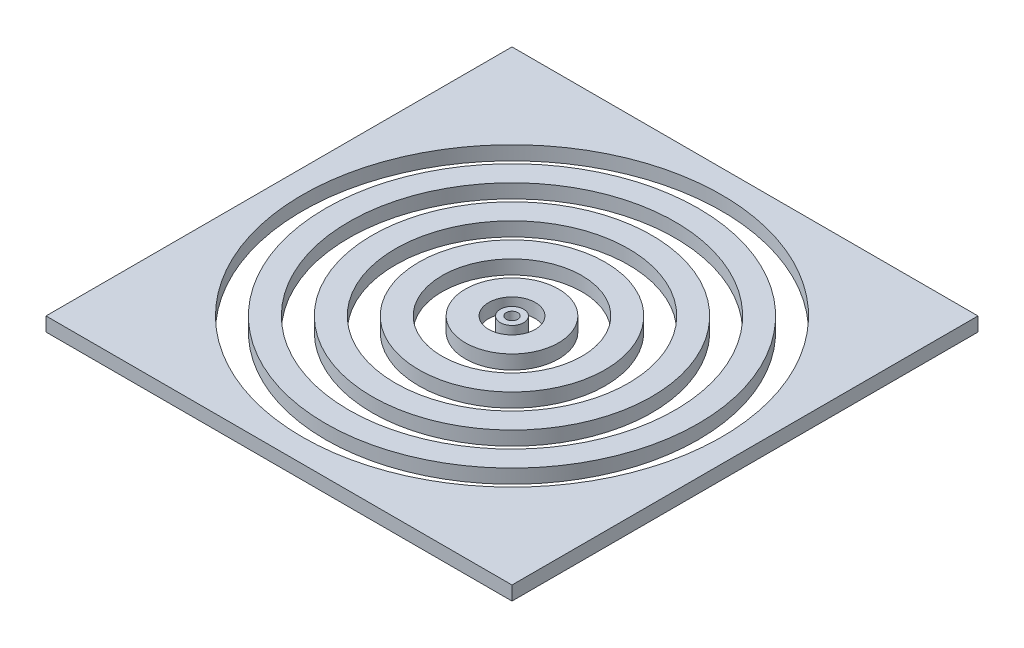
SolidWorks part; units mm, degrees
ref_plane "Front Plane" through (0, 0, 0) normal (0, 0, 1) x (1, 0, 0)
ref_plane "Top Plane" through (0, 0, 0) normal (0, 1, 0) x (1, 0, 0)
ref_plane "Right Plane" through (0, 0, 0) normal (1, 0, 0) x (0, 0, -1)
sketch "Sketch1" plane through (0, 0, 0) normal (0, 1, 0) x (1, 0, 0)
  line L1 (0, 0) -> (100, 0)
  line L2 (0, 0) -> (0, 100)
  line L3 (0, 100) -> (100, 100)
  line L4 (100, 0) -> (100, 100)
  dimension "D1" = 100
  dimension "D2" = 100
extrude "Boss-Extrude1" add sketch "Sketch1" along normal blind 3
sketch "Sketch2" plane through (0, 3, 0) normal (0, 1, 0) x (1, 0, 0)
  circle A0 centre (50, 50) radius 45
  dimension "D1" = 90
extrude "Cut-Extrude1" cut sketch "Sketch2" against normal blind 3
sketch "Sketch3" plane through (0, 3, 0) normal (0, 1, 0) x (1, 0, 0)
  circle A0 centre (50, 50) radius 40
  dimension "D1" = 80
extrude "Boss-Extrude2" add sketch "Sketch3" against normal blind 3 separate body
sketch "Sketch4" plane through (0, 3, 0) normal (0, 1, 0) x (1, 0, 0)
  circle A0 centre (50, 50) radius 35
  dimension "D1" = 70
extrude "Cut-Extrude2" cut sketch "Sketch4" against normal blind 3
sketch "Sketch5" plane through (0, 3, 0) normal (0, 1, 0) x (1, 0, 0)
  circle A0 centre (50, 50) radius 30
  dimension "D1" = 60
extrude "Boss-Extrude3" add sketch "Sketch5" against normal blind 3 separate body
sketch "Sketch6" plane through (0, 3, 0) normal (0, 1, 0) x (1, 0, 0)
  circle A0 centre (50, 50) radius 25
  dimension "D1" = 50
extrude "Cut-Extrude3" cut sketch "Sketch6" against normal blind 3
sketch "Sketch7" plane through (0, 3, 0) normal (0, 1, 0) x (1, 0, 0)
  circle A0 centre (50, 50) radius 20
  dimension "D1" = 40
extrude "Boss-Extrude4" add sketch "Sketch7" against normal blind 3 separate body
sketch "Sketch8" plane through (0, 3, 0) normal (0, 1, 0) x (1, 0, 0)
  circle A0 centre (50, 50) radius 15
  dimension "D1" = 30
extrude "Cut-Extrude4" cut sketch "Sketch8" against normal blind 3
sketch "Sketch9" plane through (0, 3, 0) normal (0, 1, 0) x (1, 0, 0)
  circle A0 centre (50, 50) radius 10
  dimension "D1" = 20
extrude "Boss-Extrude5" add sketch "Sketch9" against normal blind 3 separate body
sketch "Sketch10" plane through (0, 3, 0) normal (0, 1, 0) x (1, 0, 0)
  circle A0 centre (50, 50) radius 5
  dimension "D1" = 10
extrude "Cut-Extrude5" cut sketch "Sketch10" against normal blind 3
sketch "Sketch11" plane through (0, 3, 0) normal (0, 1, 0) x (1, 0, 0)
  circle A0 centre (50, 50) radius 2.5
  dimension "D1" = 5
extrude "Boss-Extrude6" add sketch "Sketch11" against normal blind 3 separate body
sketch "Sketch12" plane through (0, 3, 0) normal (0, 1, 0) x (1, 0, 0)
  circle A0 centre (50, 50) radius 1.25
  dimension "D1" = 2.5
extrude "Cut-Extrude6" cut sketch "Sketch12" against normal blind 3
